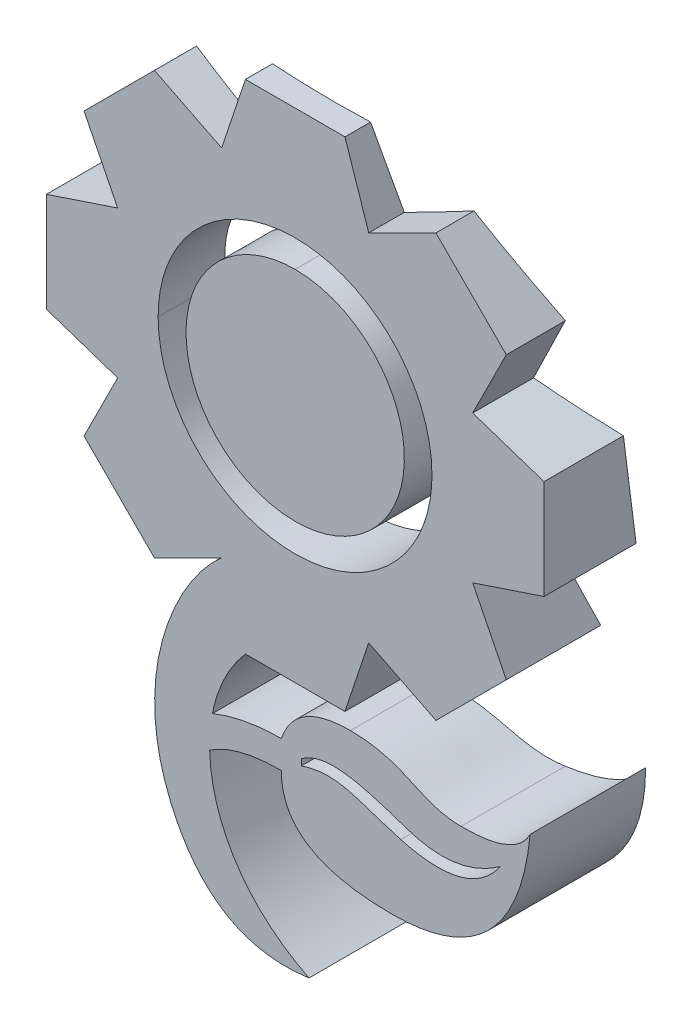
SolidWorks part; units mm, degrees
ref_plane "Plano frontal" through (0, 0, 0) normal (0, 0, 1) x (1, 0, 0)
ref_plane "Plano superior" through (0, 0, 0) normal (0, 1, 0) x (1, 0, 0)
ref_plane "Plano direito" through (0, 0, 0) normal (1, 0, 0) x (0, 0, -1)
ref_plane "Plano1" through (0, 20, 0) normal (0, 1, 0) x (1, 0, 0)
sketch "Model" plane through (0, 0, 0) normal (0, 0, 1) x (1, 0, 0)
  line L0 (8.9913, 20.9445) -> (6.2631, 21.8539)
  line L1 (6.2631, 21.8539) -> (7.5492, 24.4259)
  line L2 (7.5492, 24.4259) -> (4.8564, 27.1186)
  line L3 (4.8564, 27.1186) -> (2.2845, 25.8327)
  line L4 (2.2845, 25.8327) -> (1.3751, 28.5607)
  line L5 (1.3751, 28.5607) -> (-2.433, 28.5607)
  line L6 (-2.433, 28.5607) -> (-3.3423, 25.8325)
  line L7 (-3.3423, 25.8325) -> (-5.9145, 27.1187)
  line L8 (-5.9145, 27.1187) -> (-8.6071, 24.4258)
  line L9 (-8.6071, 24.4258) -> (-7.3212, 21.8538)
  line L10 (-7.3212, 21.8538) -> (-10.0491, 20.9445)
  line L11 (-10.0491, 20.9445) -> (-10.0491, 17.1364)
  line L12 (-10.0491, 17.1364) -> (-7.3212, 16.2271)
  line L13 (-7.3212, 16.2271) -> (-8.6073, 13.655)
  line L14 (-8.6073, 13.655) -> (-5.9144, 10.9623)
  line L15 (-5.9144, 10.9623) -> (-3.3423, 12.2483)
  line L16 (-2.433, 9.5202) -> (1.3751, 9.5202)
  line L17 (1.3751, 9.5202) -> (2.2845, 12.2483)
  line L18 (2.2845, 12.2483) -> (4.8564, 10.9622)
  line L19 (4.8564, 10.9622) -> (7.5492, 13.6551)
  line L20 (7.5492, 13.6551) -> (6.2631, 16.227)
  line L21 (6.2631, 16.227) -> (8.9913, 17.1364)
  line L22 (8.9913, 17.1364) -> (8.9913, 20.9445)
  line L23 (-0.2956, 6.8795) -> (-0.2956, 7.1177)
  spline S0 degree 3 poles (-0.5289, 23.2167) (1.7775, 23.2167) (3.6473, 21.3468) (3.6473, 19.0405) (3.6473, 16.7341) (1.7775, 14.8643) (-0.5289, 14.8643) knots 2 2 2 2 3 3 3 4 4 4 4
  spline S1 degree 3 poles (-0.5289, 14.8643) (-2.8353, 14.8643) (-4.7051, 16.7341) (-4.7051, 19.0405) (-4.7051, 21.3468) (-2.8353, 23.2167) (-0.5289, 23.2167) knots 0 0 0 0 1 1 1 2 2 2 2
  spline S2 degree 3 poles (-2.433, 9.5202) (-3.0829, 8.7817) (-3.5101, 7.8781) (-3.696, 6.9132) knots 0 0 0 0 0.279281 0.279281 0.279281 0.279281
  spline S3 degree 2 poles (0, 0) (-3.7023, -0.5289) (-5.289, 3.1734) knots 1 1 1 2 2 2
  spline S4 degree 3 poles (-5.289, 3.1734) (-6.8757, 6.8757) (-5.0979, 10.7451) (-3.3423, 12.2483) knots 2 2 2 2 3 3 3 3
  spline S5 degree 2 poles (-3.696, 6.9132) (-2.4998, 7.4046) (-1.0578, 7.4047) knots 0.318418 0.318418 0.318418 1 1 1
  spline S6 degree 2 poles (-1.0578, 7.4047) (-0.5289, 8.9914) (1.5867, 8.9913) knots 1 1 1 2 2 2
  spline S7 degree 3 poles (1.5867, 8.9913) (3.7023, 8.9913) (4.2312, 7.9335) (5.8179, 7.9335) knots 2 2 2 2 3 3 3 3
  spline S8 degree 3 poles (5.8179, 7.9335) (6.3468, 7.9335) (7.9335, 7.9335) (8.4624, 8.9913) knots 3 3 3 3 4 4 4 4
  spline S9 degree 2 poles (8.4624, 8.9913) (7.9335, 3.7023) (3.1734, 3.7023) knots 4 4 4 5 5 5
  spline S10 degree 2 poles (3.1734, 3.7023) (-1.0578, 3.7023) (-1.0578, 6.3468) knots 5 5 5 6 6 6
  spline S11 degree 2 poles (-1.0578, 6.3468) (-2.7796, 6.3468) (-3.8007, 5.6462) knots 6 6 6 6.813847 6.813847 6.813847
  spline S12 degree 3 poles (-0.2956, 7.1177) (0.6569, 7.832) (2.0374, 7.4084) (3.7526, 6.8194) knots 0 0 0 0 1 1 1 1
  spline S13 degree 2 poles (3.7526, 6.8194) (5.6576, 6.1652) (7.3244, 7.3558) knots 1 1 1 2 2 2
  spline S14 degree 2 poles (7.3244, 7.3558) (6.1338, 5.6288) (3.5144, 6.3432) knots 2 2 2 3 3 3
  spline S15 degree 3 poles (3.5144, 6.3432) (1.842, 6.7992) (1.1332, 7.3558) (-0.2956, 6.8795) knots 3 3 3 3 4 4 4 4
  spline S16 degree 3 poles (-5.7724, 19.0239) (-5.7724, 16.1306) (-3.427, 13.7852) (-0.5337, 13.7852) (2.3596, 13.7852) (4.7051, 16.1306) (4.7051, 19.0239) knots 2 2 2 2 3 3 3 4 4 4 4
  spline S17 degree 3 poles (4.7051, 19.0239) (4.7051, 21.9172) (2.3596, 24.2627) (-0.5337, 24.2627) (-3.427, 24.2627) (-5.7724, 21.9172) (-5.7724, 19.0239) knots 0 0 0 0 1 1 1 2 2 2 2
  spline S18 degree 3 poles (-3.8007, 5.6462) (-3.7484, 3.4978) (-2.5428, 1.2714) (0, 0) knots 0.39905 0.39905 0.39905 0.39905 1 1 1 1
  dimension "D1" = 28.5607
extrude "Ressalto-extrusão1" add sketch "Model" along normal blind 5 contours S18 S11 S10 S9 S8 S7 S6 S5 S2 L16 L17 L18 L19 L20 L21 L22 L0 L1 L2 L3 L4 L5 L6 L7 L8 L9 L10 L11 L12 L13 L14 L15 S4 S3 S17 S16 S14 S15 L23 S12 S13 | S1 S0
sketch "Esboço6" plane through (0, 20, 0) normal (0, 1, 0) x (1, 0, 0)
  circle A0 centre (0, 32.6958) radius 35.6888
extrude "Corte-extrusão3" cut sketch "Esboço6" along normal blind 77.48 draft 7 and the other way blind 77.48 draft 7 draft outward yes
